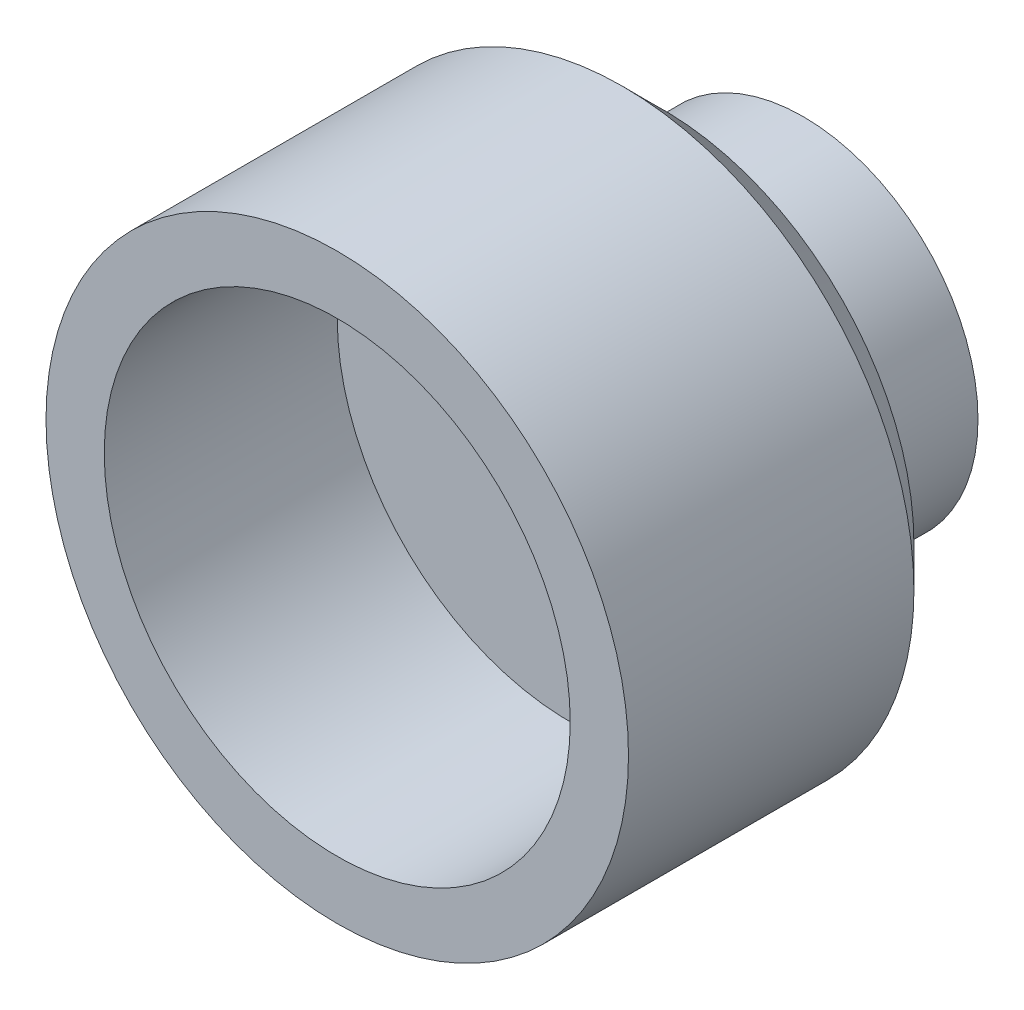
SolidWorks part; units mm, degrees
ref_plane "Front Plane" through (0, 0, 0) normal (0, 0, 1) x (1, 0, 0)
ref_plane "Top Plane" through (0, 0, 0) normal (0, 1, 0) x (1, 0, 0)
ref_plane "Right Plane" through (0, 0, 0) normal (1, 0, 0) x (0, 0, -1)
sketch "Sketch1" plane through (0, 0, 0) normal (1, 0, 0) x (0, 0, -1)
  line L0 (-20.7004, 0) -> (18.1553, 0) construction
  line L1 (2.75, 0) -> (-2.75, 0) construction
  line L2 (0, 55) -> (0, -55) construction
  line L3 (0, 2.5) -> (2.8, 2.5)
  line L4 (2.8, 2.5) -> (2.8, 1.5)
  line L5 (2.8, 1.5) -> (4, 1.5)
  line L6 (4, 1.5) -> (4, 0.5)
  line L7 (4, 0.5) -> (2, 0.5)
  line L8 (2, 0.5) -> (2, 2)
  line L9 (2, 2) -> (0, 2)
  line L10 (0, 2) -> (0, 2.5)
  dimension "D1" = 5
  dimension "D2" = 4
  dimension "D3" = 2
  dimension "D4" = 0.8
  dimension "D5" = 2
  dimension "D6" = 1
  dimension "D7" = 1
revolve "Revolve1" add sketch "Sketch1" angle 360 about L0
chamfer "Fase1" distance 0.35 angle 45 1 edges at (2.5, 0, -2.8)
